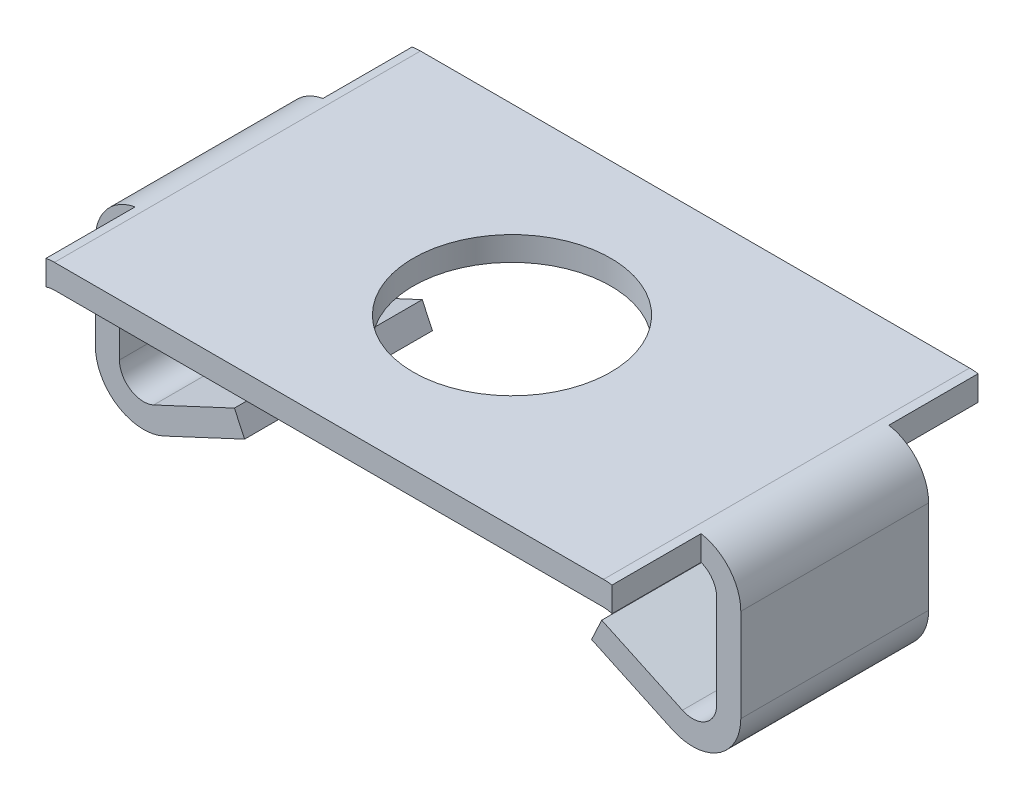
SolidWorks part; units mm, degrees
ref_plane "前视基准面" through (0, 0, 0) normal (0, 0, 1) x (1, 0, 0)
ref_plane "上视基准面" through (0, 0, 0) normal (0, 1, 0) x (1, 0, 0)
ref_plane "右视基准面" through (0, 0, 0) normal (1, 0, 0) x (0, 0, -1)
sketch "草图1" plane through (0, 0, 0) normal (0, 0, 1) x (1, 0, 0)
  line B0 (-7.3482, -6.1105) -> (-10.6995, -7.6732)
  line B1 (-13.5447, -5.8606) -> (-13.5447, -2)
  line B2 (-11.5447, 0) -> (11.2553, 0)
  line B3 (13.2553, -2) -> (13.2553, -5.8606)
  line B4 (10.41, -7.6732) -> (7.0587, -6.1105)
  line B5 (-7.7708, -5.2042) -> (-11.1221, -6.7669)
  line B6 (-12.5447, -5.8606) -> (-12.5447, -2)
  line B7 (-11.5447, -1) -> (11.2553, -1)
  line B8 (12.2553, -2) -> (12.2553, -5.8606)
  line B9 (10.8326, -6.7669) -> (7.4813, -5.2042)
  line B10 (-7.3482, -6.1105) -> (-7.7708, -5.2042)
  line B11 (7.4813, -5.2042) -> (7.0587, -6.1105)
  arc B12 (-13.5447, -5.8606) -> (-10.6995, -7.6732) centre (-11.5447, -5.8606) ccw
  arc B13 (-11.5447, 0) -> (-13.5447, -2) centre (-11.5447, -2) ccw
  arc B14 (13.2553, -2) -> (11.2553, 0) centre (11.2553, -2) ccw
  arc B15 (10.41, -7.6732) -> (13.2553, -5.8606) centre (11.2553, -5.8606) ccw
  arc B16 (-12.5447, -5.8606) -> (-11.1221, -6.7669) centre (-11.5447, -5.8606) ccw
  arc B17 (-11.5447, -1) -> (-12.5447, -2) centre (-11.5447, -2) ccw
  arc B18 (12.2553, -2) -> (11.2553, -1) centre (11.2553, -2) ccw
  arc B19 (10.8326, -6.7669) -> (12.2553, -5.8606) centre (11.2553, -5.8606) ccw
sketch_block_instance "A$C20CA02BE-1"
sketch_block "A$C20CA02BE"
extrude "凸台-拉伸1" add sketch "草图1" along normal mid plane 15.2
sketch "草图3" plane through (0, 0, 7.6) normal (0, 0, 1) x (1, 0, 0)
  line L0 (-0.1447, -1) -> (-0.1447, -6.3247) construction
  line L1 (-11.5447, -1) -> (11.2553, -1) construction
  line L2 (-11.8947, -3.2921) -> (-5.6507, -3.2921)
  line L3 (-5.6507, -8.7891) -> (-21.3044, -8.7891)
  line L4 (-11.8947, -3.2921) -> (-11.8947, 0.9442)
  line L5 (-11.8947, 0.9442) -> (-21.3044, 0.9442)
  line L6 (-21.3044, -8.7891) -> (-21.3044, 0.9442)
  line L7 (-5.6507, -3.2921) -> (-5.6507, -8.7891)
  line L8 (5.3612, -3.2921) -> (5.3612, -8.7891)
  line L9 (21.0149, -8.7891) -> (21.0149, 0.9442)
  line L10 (11.6053, 0.9442) -> (21.0149, 0.9442)
  line L11 (11.6053, -3.2921) -> (11.6053, 0.9442)
  line L12 (5.3612, -8.7891) -> (21.0149, -8.7891)
  line L13 (11.6053, -3.2921) -> (5.3612, -3.2921)
  dimension "D1" = 11.75
extrude "切除-拉伸1" cut sketch "草图3" against normal blind 3.7
ref_plane "基准面2" through (0, 0, 0) normal (0, 0, 1) x (1, 0, 0)
mirror "镜向1" about plane through (0, 0, 0) normal (0, 0, 1) of "切除-拉伸1"
sketch "草图4" plane through (0, 0, 0) normal (0, 1, 0) x (1, 0, 0)
  point P0 (-0.1447, 0)
sketch "草图5" plane through (0, 0, 0) normal (0, 1, 0) x (1, 0, 0)
  circle A0 centre (-0.1447, 0) radius 4.1
extrude "切除-拉伸2" cut sketch "草图5" against normal blind 3.7
